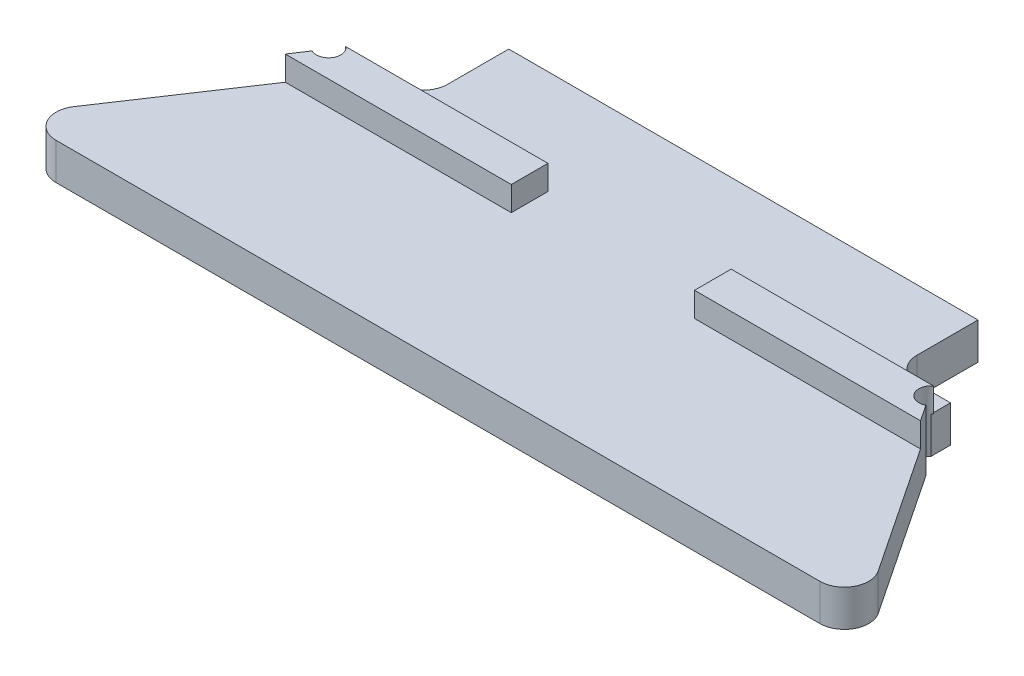
SolidWorks part; units mm, degrees
material "99.5% Aluminum Oxide"
ref_plane "Front Plane" through (0, 0, 0) normal (0, 0, 1) x (1, 0, 0)
ref_plane "Top Plane" through (0, 0, 0) normal (0, 1, 0) x (1, 0, 0)
ref_plane "Right Plane" through (0, 0, 0) normal (1, 0, 0) x (0, 0, -1)
sketch "Sketch1" plane through (0, 0, 0) normal (0, 1, 0) x (1, 0, 0)
  line L1 (-25, -12.5) -> (25, -12.5)
  line L2 (-25, -12.5) -> (-25, 12.5) construction
  line L3 (-25, 12.5) -> (25, 12.5) construction
  line L4 (25, -12.5) -> (25, 12.5) construction
  line L5 (-25, -12.5) -> (25, 12.5) construction
  line L6 (-25, 12.5) -> (25, -12.5) construction
  line L8 (-19.2062, 12.5) -> (19.2062, 12.5)
  line L11 (0, 11.2271) -> (0, -49988.7729) construction
  line L12 (-24.2062, 2.5) -> (-25, 2.5)
  line L13 (24.2062, 2.5) -> (25, 2.5)
  line L14 (-25, 2.5) -> (-35, -12.5)
  line L15 (-35, -12.5) -> (-25, -12.5)
  line L16 (25, 2.5) -> (35, -12.5)
  line L17 (35, -12.5) -> (25, -12.5)
  line L18 (-24.2062, 2.5) -> (-24.2062, 5.5)
  line L19 (-24.2062, 5.5) -> (-19.2062, 5.5)
  line L20 (-19.2062, 5.5) -> (-19.2062, 12.5)
  line L21 (24.2062, 2.5) -> (24.2062, 5.5)
  line L22 (24.2062, 5.5) -> (19.2062, 5.5)
  line L23 (19.2062, 5.5) -> (19.2062, 12.5)
  point P0 (0, 0)
  point P14 (0, 12.5)
  dimension "D1" = 25
  dimension "D2" = 50
  dimension "D3" = 10
  dimension "D4" = 15
  dimension "D5" = 0.7937
  dimension "D6" = 3
  dimension "D7" = 5
extrude "Boss-Extrude1" add sketch "Sketch1" along normal mid plane 3
sketch "Sketch4" plane through (0, 1.5, 0) normal (0, 1, 0) x (1, 0, 0)
  line L0 (-24.2062, 2.5) -> (-25, 2.5) construction
  line L2 (24.2062, 2.5) -> (23.9562, 2.5)
  line L3 (0, 0) -> (0, 50000) construction
  line L4 (-24.2062, 5.5) -> (-23.9562, 5.5)
  line L5 (-24.2062, 5.5) -> (-24.2062, 2.5)
  line L6 (-24.2062, 2.5) -> (-23.9562, 2.5)
  line L7 (-23.9562, 5.5) -> (-23.9562, 2.5)
  line L12 (23.9562, 5.5) -> (23.9562, 2.5)
  line L13 (24.2062, 5.5) -> (23.9562, 5.5)
  line L14 (24.2062, 5.5) -> (24.2062, 2.5)
  dimension "D1" = 0.25
extrude "Cut-Extrude4" cut sketch "Sketch4" against normal through all both and the other way through all
sketch "Sketch5" plane through (0, 1.5, 0) normal (0, 1, 0) x (1, 0, 0)
  line L0 (-23.9562, 2.5) -> (-24.6634, 3.2071) construction
  line L1 (-23.9562, 2.5) -> (-23.9562, 5.5) construction
  line L2 (-23.9562, 2.5) -> (-25, 2.5) construction
  line L3 (0, 0) -> (0, 50000) construction
  circle A0 centre (-24.6634, 3.2071) radius 1
  circle A1 centre (24.6634, 3.2071) radius 1
  point P2 (-23.9562, 3.9142)
  point P3 (-25.3705, 2.5)
  point P4 (-23.9562, 2.5)
  dimension "D1" = 2
  dimension "D2" = 45
extrude "Cut-Extrude5" cut sketch "Sketch5" against normal through all both and the other way through all
fillet "Fillet5" radius 2 4 edges at (35, 0, 12.5) (-35, 0, 12.5) (19.2062, 0, -5.5) (-19.2062, 0, -5.5)
sketch "Sketch6" plane through (0, 1.5, 0) normal (0, 1, 0) x (1, 0, 0)
  line L1 (-24.054, 4) -> (-7.5, 4)
  line L2 (-7.5, 4) -> (-7.5, 1)
  line L3 (-7.5, 1) -> (-26, 1)
  line L5 (-25.1213, 2.3181) -> (-26, 1)
  line L6 (-25.1213, 2.3181) -> (-32.9271, -9.3906) construction
  line L8 (32.9271, -9.3906) -> (25.1213, 2.3181) construction
  line L9 (26, 1) -> (25.1213, 2.3181)
  line L10 (24.054, 4) -> (7.5, 4)
  line L11 (7.5, 4) -> (7.5, 1)
  line L12 (7.5, 1) -> (26, 1)
  line L13 (19.2062, 12.5) -> (-19.2062, 12.5) construction
  arc A0 (-25.1213, 2.3181) -> (-23.9562, 3.9142) centre (-24.6634, 3.2071) ccw construction
  arc A1 (23.9562, 3.9142) -> (25.1213, 2.3181) centre (24.6634, 3.2071) ccw construction
  arc A2 (-24.054, 4) -> (-25.1213, 2.3181) centre (-24.6634, 3.2071) cw
  arc A3 (24.054, 4) -> (25.1213, 2.3181) centre (24.6634, 3.2071) ccw
  dimension "D1" = 8.5
  dimension "D2" = 15
  dimension "D3" = 3
extrude "Boss-Extrude2" add sketch "Sketch6" along normal blind 2
